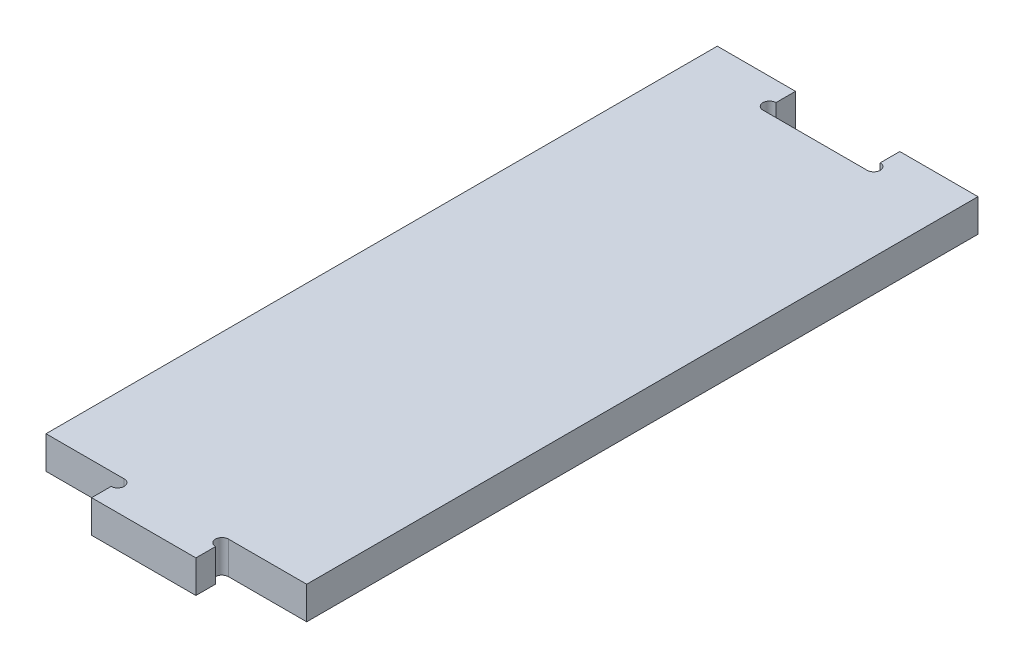
SolidWorks part; units mm, degrees
material "유리"
ref_plane "정면" through (0, 0, 0) normal (0, 0, 1) x (1, 0, 0)
ref_plane "윗면" through (0, 0, 0) normal (0, 1, 0) x (1, 0, 0)
ref_plane "우측면" through (0, 0, 0) normal (1, 0, 0) x (0, 0, -1)
sketch "스케치1" plane through (0, 0, 0) normal (0, 1, 0) x (1, 0, 0)
  line L1 (0, 0) -> (40, 0)
  line L2 (0, 0) -> (0, 103)
  line L3 (0, 103) -> (40, 103)
  line L4 (40, 0) -> (40, 103)
  dimension "D1" = 103
  dimension "D2" = 40
extrude "보스-돌출1" add sketch "스케치1" along normal blind 5
sketch "스케치2" plane through (0, 5, 0) normal (0, 1, 0) x (1, 0, 0)
  line L0 (40, 103) -> (0, 103) construction
  line L1 (12, 103) -> (28, 103)
  line L2 (12, 103) -> (12, 98)
  line L3 (12, 98) -> (28, 98)
  line L4 (28, 103) -> (28, 98)
  line L5 (40, 0) -> (40, 103) construction
  line L6 (0, 103) -> (0, 0) construction
  dimension "D1" = 12
  dimension "D2" = 12
  dimension "D3" = 5
extrude "컷-돌출1" cut sketch "스케치2" against normal blind 5
sketch "스케치3" plane through (0, 5, 0) normal (0, 1, 0) x (1, 0, 0)
  line L0 (0, 0) -> (40, 0) construction
  line L1 (12, 0) -> (28, 0)
  line L2 (12, 0) -> (12, -5)
  line L3 (12, -5) -> (28, -5)
  line L4 (28, 0) -> (28, -5)
  line L5 (40, 0) -> (40, 103) construction
  line L6 (0, 103) -> (0, 0) construction
  dimension "D1" = 12
  dimension "D2" = 5
  dimension "D3" = 12
extrude "보스-돌출3" add sketch "스케치3" against normal blind 5
sketch "스케치4" plane through (0, 5, 0) normal (0, 1, 0) x (1, 0, 0)
  line L0 (12, 0) -> (12, -5) construction
  line L1 (28, -5) -> (28, 0) construction
  line L2 (12, 103) -> (12, 98) construction
  line L3 (28, 98) -> (28, 103) construction
  circle A0 centre (12, -1) radius 1
  circle A1 centre (28, -1) radius 1
  circle A2 centre (12, 99) radius 1
  circle A3 centre (28, 99) radius 1
  dimension "D1" = 2
extrude "컷-돌출2" cut sketch "스케치4" against normal blind 10
